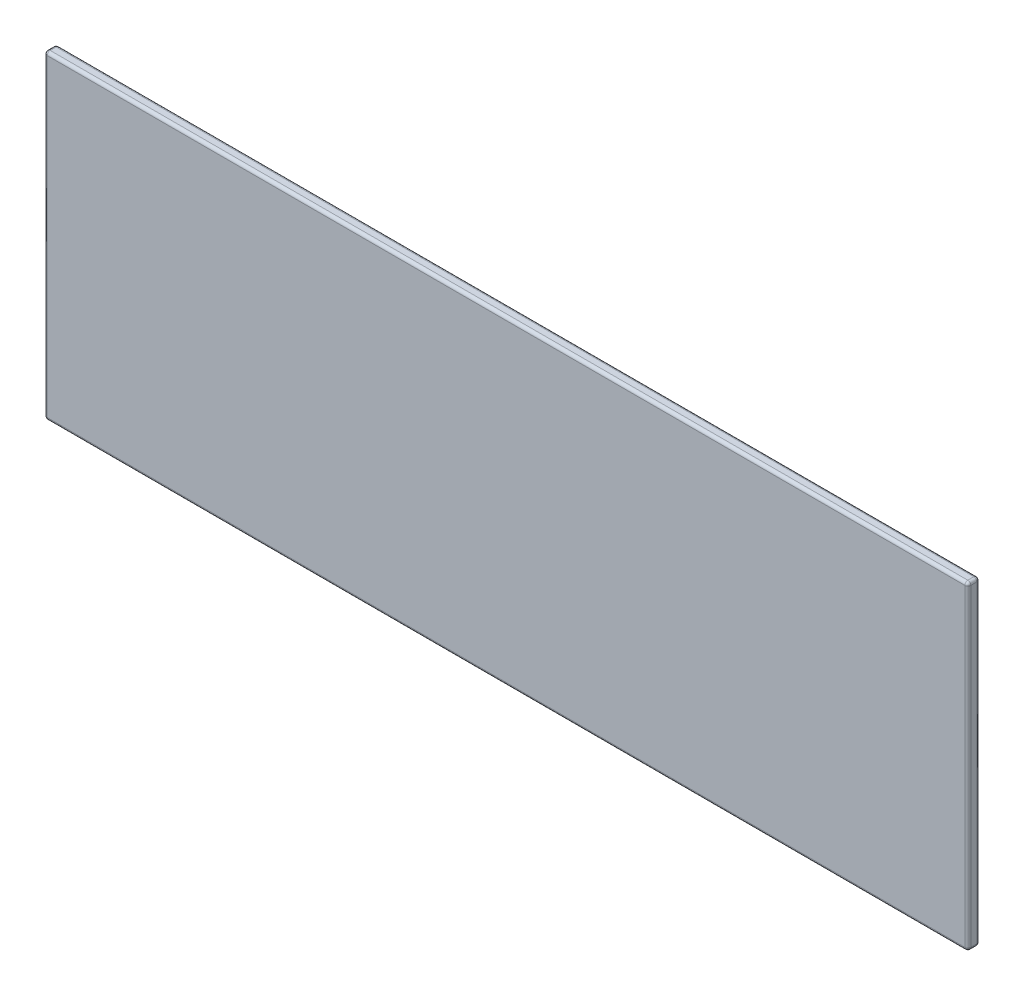
SolidWorks part; units mm, degrees
ref_plane "Front Plane" through (0, 0, 0) normal (0, 0, 1) x (1, 0, 0)
ref_plane "Top Plane" through (0, 0, 0) normal (0, 1, 0) x (1, 0, 0)
ref_plane "Right Plane" through (0, 0, 0) normal (1, 0, 0) x (0, 0, -1)
sketch "Sketch1" plane through (0, 0, 0) normal (0, 0, 1) x (1, 0, 0)
  line L1 (-77.35, -26.75) -> (77.35, -26.75)
  line L2 (-77.35, -26.75) -> (-77.35, 26.75)
  line L3 (-77.35, 26.75) -> (77.35, 26.75)
  line L4 (77.35, -26.75) -> (77.35, 26.75)
  line L5 (-77.35, -26.75) -> (77.35, 26.75) construction
  line L6 (-77.35, 26.75) -> (77.35, -26.75) construction
  point P0 (0, 0)
  dimension "D1" = 154.7
  dimension "D2" = 53.5
extrude "Boss-Extrude1" add sketch "Sketch1" along normal blind 2
fillet "Fillet1" radius 0.5 12 edges at (0, -26.75, 2) (0, -26.75, 0) (-77.35, 0, 2) (-77.35, -26.75, 1) (-77.35, 0, 0) (0, 26.75, 2) (-77.35, 26.75, 1) (0, 26.75, 0) (77.35, -26.75, 1) (77.35, 0, 2) (77.35, 26.75, 1) (77.35, 0, 0)
